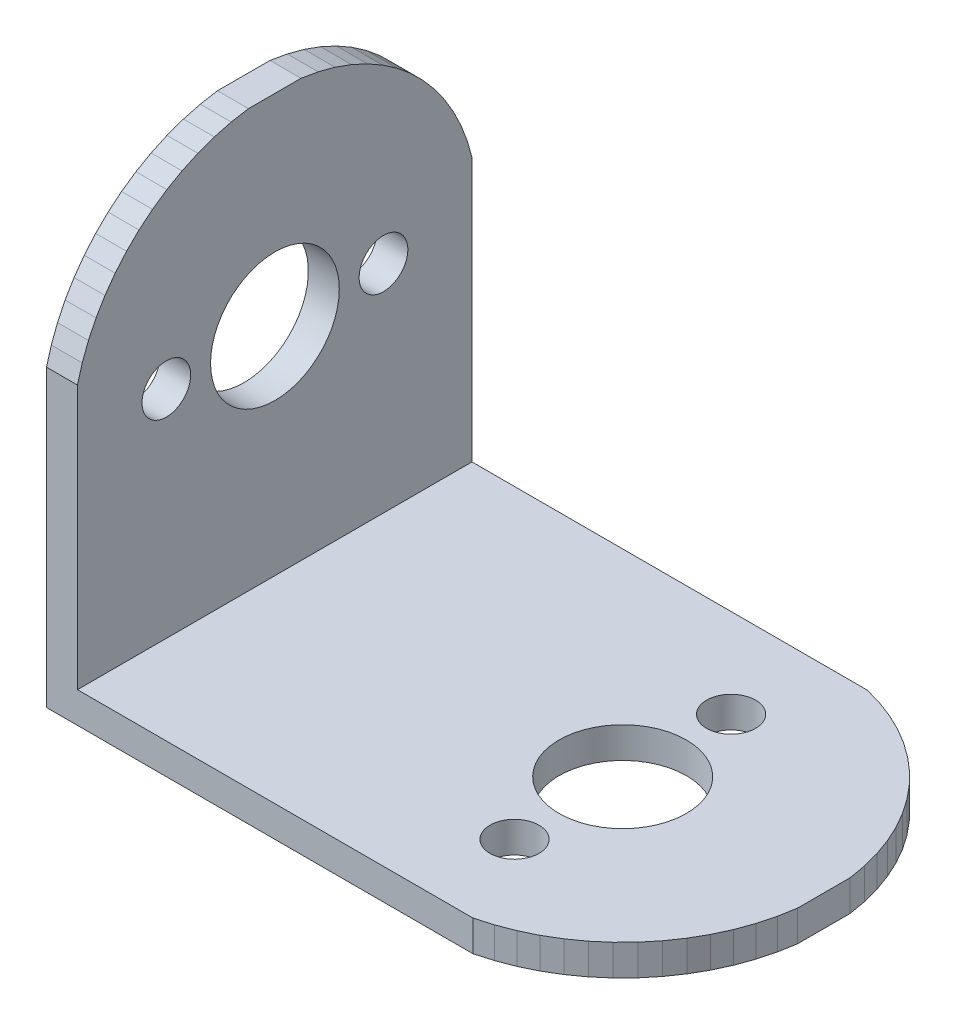
SolidWorks part; units mm, degrees
ref_plane "Alzado" through (0, 0, 0) normal (0, 0, 1) x (1, 0, 0)
ref_plane "Planta" through (0, 0, 0) normal (0, 1, 0) x (1, 0, 0)
ref_plane "Vista lateral" through (0, 0, 0) normal (1, 0, 0) x (0, 0, -1)
ref_plane "Plano1" through (-18.75, 0, 0) normal (-1, 0, 0) x (0, -1, 0)
sketch "Croquis1" plane through (-18.75, 0, 0) normal (-1, 0, 0) x (0, -1, 0)
  line L0 (-19.0529, -77.75) -> (-19.0529, -52.25)
  line L1 (-19.0529, -52.25) -> (-20.1385, -52.5599)
  line L2 (-20.1385, -52.5599) -> (-21.1933, -52.9621)
  line L3 (-21.1933, -52.9621) -> (-22.2097, -53.4535)
  line L4 (-22.2097, -53.4535) -> (-23.18, -54.0305)
  line L5 (-23.18, -54.0305) -> (-24.0971, -54.6889)
  line L6 (-24.0971, -54.6889) -> (-24.9542, -55.4237)
  line L7 (-24.9542, -55.4237) -> (-25.7448, -56.2295)
  line L8 (-25.7448, -56.2295) -> (-26.4632, -57.1004)
  line L9 (-26.4632, -57.1004) -> (-27.104, -58.0298)
  line L10 (-27.104, -58.0298) -> (-27.6625, -59.0109)
  line L11 (-27.6625, -59.0109) -> (-28.1345, -60.0365)
  line L12 (-28.1345, -60.0365) -> (-28.5165, -61.0988)
  line L13 (-28.5165, -61.0988) -> (-28.8057, -62.1901)
  line L14 (-28.8057, -62.1901) -> (-29, -63.3022)
  line L15 (-29, -63.3022) -> (-29, -66.6978)
  line L16 (-29, -66.6978) -> (-28.8057, -67.8099)
  line L17 (-28.8057, -67.8099) -> (-28.5165, -68.9012)
  line L18 (-28.5165, -68.9012) -> (-28.1345, -69.9635)
  line L19 (-28.1345, -69.9635) -> (-27.6625, -70.9891)
  line L20 (-27.6625, -70.9891) -> (-27.104, -71.9702)
  line L21 (-27.104, -71.9702) -> (-26.4632, -72.8996)
  line L22 (-26.4632, -72.8996) -> (-25.7448, -73.7705)
  line L23 (-25.7448, -73.7705) -> (-24.9542, -74.5763)
  line L24 (-24.9542, -74.5763) -> (-24.0971, -75.3111)
  line L25 (-24.0971, -75.3111) -> (-23.18, -75.9695)
  line L26 (-23.18, -75.9695) -> (-22.2097, -76.5465)
  line L27 (-22.2097, -76.5465) -> (-21.1933, -77.0379)
  line L28 (-21.1933, -77.0379) -> (-20.1385, -77.4401)
  line L29 (-20.1385, -77.4401) -> (-19.0529, -77.75)
extrude "Saliente-Extruir1" add sketch "Croquis1" against normal blind 2
sketch "Croquis2" plane through (0, 19.0529, 0) normal (0, -1, 0) x (1, 0, 0)
  line L0 (-16.75, -52.25) -> (-16.75, -77.75)
  line L1 (-16.75, -77.75) -> (-18.75, -77.75)
  line L2 (-18.75, -77.75) -> (-18.75, -52.25)
  line L3 (-18.75, -52.25) -> (-16.75, -52.25)
extrude "Saliente-Extruir2" add sketch "Croquis2" along normal blind 17.0529
sketch "Croquis3" plane through (0, 2, 0) normal (0, -1, 0) x (1, 0, 0)
  line L0 (8.8029, -77.75) -> (-18.75, -77.75)
  line L1 (-18.75, -77.75) -> (-18.75, -52.25)
  line L2 (-18.75, -52.25) -> (8.8029, -52.25)
  line L3 (8.8029, -52.25) -> (9.8885, -52.5599)
  line L4 (9.8885, -52.5599) -> (10.9433, -52.9621)
  line L5 (10.9433, -52.9621) -> (11.9597, -53.4535)
  line L6 (11.9597, -53.4535) -> (12.93, -54.0305)
  line L7 (12.93, -54.0305) -> (13.8471, -54.6889)
  line L8 (13.8471, -54.6889) -> (14.7042, -55.4237)
  line L9 (14.7042, -55.4237) -> (15.4948, -56.2295)
  line L10 (15.4948, -56.2295) -> (16.2132, -57.1004)
  line L11 (16.2132, -57.1004) -> (16.854, -58.0298)
  line L12 (16.854, -58.0298) -> (17.4125, -59.0109)
  line L13 (17.4125, -59.0109) -> (17.8845, -60.0365)
  line L14 (17.8845, -60.0365) -> (18.2665, -61.0988)
  line L15 (18.2665, -61.0988) -> (18.5557, -62.1901)
  line L16 (18.5557, -62.1901) -> (18.75, -63.3022)
  line L17 (18.75, -63.3022) -> (18.75, -66.6978)
  line L18 (18.75, -66.6978) -> (18.5557, -67.8099)
  line L19 (18.5557, -67.8099) -> (18.2665, -68.9012)
  line L20 (18.2665, -68.9012) -> (17.8845, -69.9635)
  line L21 (17.8845, -69.9635) -> (17.4125, -70.9891)
  line L22 (17.4125, -70.9891) -> (16.854, -71.9702)
  line L23 (16.854, -71.9702) -> (16.2132, -72.8996)
  line L24 (16.2132, -72.8996) -> (15.4948, -73.7705)
  line L25 (15.4948, -73.7705) -> (14.7042, -74.5763)
  line L26 (14.7042, -74.5763) -> (13.8471, -75.3111)
  line L27 (13.8471, -75.3111) -> (12.93, -75.9695)
  line L28 (12.93, -75.9695) -> (11.9597, -76.5465)
  line L29 (11.9597, -76.5465) -> (10.9433, -77.0379)
  line L30 (10.9433, -77.0379) -> (9.8885, -77.4401)
  line L31 (9.8885, -77.4401) -> (8.8029, -77.75)
extrude "Saliente-Extruir3" add sketch "Croquis3" along normal blind 2
sketch "Croquis4" plane through (-18.75, 0, 0) normal (-1, 0, 0) x (0, 0, 1)
  line L0 (-67.8848, 13.2291) -> (-67.403, 12.8022)
  line L1 (-67.403, 12.8022) -> (-66.8589, 12.4582)
  line L2 (-66.8589, 12.4582) -> (-66.2667, 12.2059)
  line L3 (-66.2667, 12.2059) -> (-65.6416, 12.0518)
  line L4 (-65.6416, 12.0518) -> (-65, 12)
  line L5 (-65, 12) -> (-64.3584, 12.0518)
  line L6 (-64.3584, 12.0518) -> (-63.7333, 12.2059)
  line L7 (-63.7333, 12.2059) -> (-63.1411, 12.4582)
  line L8 (-63.1411, 12.4582) -> (-62.597, 12.8022)
  line L9 (-62.597, 12.8022) -> (-62.1152, 13.2291)
  line L10 (-62.1152, 13.2291) -> (-61.7081, 13.7277)
  line L11 (-61.7081, 13.7277) -> (-61.3862, 14.2852)
  line L12 (-61.3862, 14.2852) -> (-61.1579, 14.8871)
  line L13 (-61.1579, 14.8871) -> (-61.0292, 15.5179)
  line L14 (-61.0292, 15.5179) -> (-61.0032, 16.1611)
  line L15 (-61.0032, 16.1611) -> (-61.0808, 16.8001)
  line L16 (-61.0808, 16.8001) -> (-61.2599, 17.4184)
  line L17 (-61.2599, 17.4184) -> (-61.5359, 18)
  line L18 (-61.5359, 18) -> (-61.9016, 18.5298)
  line L19 (-61.9016, 18.5298) -> (-62.3475, 18.994)
  line L20 (-62.3475, 18.994) -> (-62.8621, 19.3808)
  line L21 (-62.8621, 19.3808) -> (-63.4321, 19.6799)
  line L22 (-63.4321, 19.6799) -> (-64.0427, 19.8838)
  line L23 (-64.0427, 19.8838) -> (-64.6781, 19.987)
  line L24 (-64.6781, 19.987) -> (-65.3219, 19.987)
  line L25 (-65.3219, 19.987) -> (-65.9573, 19.8838)
  line L26 (-65.9573, 19.8838) -> (-66.5679, 19.6799)
  line L27 (-66.5679, 19.6799) -> (-67.1379, 19.3808)
  line L28 (-67.1379, 19.3808) -> (-67.6525, 18.994)
  line L29 (-67.6525, 18.994) -> (-68.0984, 18.5298)
  line L30 (-68.0984, 18.5298) -> (-68.4641, 18)
  line L31 (-68.4641, 18) -> (-68.7401, 17.4184)
  line L32 (-68.7401, 17.4184) -> (-68.9192, 16.8001)
  line L33 (-68.9192, 16.8001) -> (-68.9968, 16.1611)
  line L34 (-68.9968, 16.1611) -> (-68.9708, 15.5179)
  line L35 (-68.9708, 15.5179) -> (-68.8421, 14.8871)
  line L36 (-68.8421, 14.8871) -> (-68.6138, 14.2852)
  line L37 (-68.6138, 14.2852) -> (-68.2919, 13.7277)
  line L38 (-68.2919, 13.7277) -> (-67.8848, 13.2291)
extrude "Cortar-Extruir1" cut sketch "Croquis4" against normal through all
sketch "Croquis5" plane through (-18.75, 0, 0) normal (-1, 0, 0) x (0, 0, 1)
  line L0 (-57.25, 14.701) -> (-56.9393, 14.9393)
  line L1 (-56.9393, 14.9393) -> (-56.701, 15.25)
  line L2 (-56.701, 15.25) -> (-56.5511, 15.6118)
  line L3 (-56.5511, 15.6118) -> (-56.5, 16)
  line L4 (-56.5, 16) -> (-56.5511, 16.3882)
  line L5 (-56.5511, 16.3882) -> (-56.701, 16.75)
  line L6 (-56.701, 16.75) -> (-56.9393, 17.0607)
  line L7 (-56.9393, 17.0607) -> (-57.25, 17.299)
  line L8 (-57.25, 17.299) -> (-57.6118, 17.4489)
  line L9 (-57.6118, 17.4489) -> (-58, 17.5)
  line L10 (-58, 17.5) -> (-58.3882, 17.4489)
  line L11 (-58.3882, 17.4489) -> (-58.75, 17.299)
  line L12 (-58.75, 17.299) -> (-59.0607, 17.0607)
  line L13 (-59.0607, 17.0607) -> (-59.299, 16.75)
  line L14 (-59.299, 16.75) -> (-59.4489, 16.3882)
  line L15 (-59.4489, 16.3882) -> (-59.5, 16)
  line L16 (-59.5, 16) -> (-59.4489, 15.6118)
  line L17 (-59.4489, 15.6118) -> (-59.299, 15.25)
  line L18 (-59.299, 15.25) -> (-59.0607, 14.9393)
  line L19 (-59.0607, 14.9393) -> (-58.75, 14.701)
  line L20 (-58.75, 14.701) -> (-58.3882, 14.5511)
  line L21 (-58.3882, 14.5511) -> (-58, 14.5)
  line L22 (-58, 14.5) -> (-57.6118, 14.5511)
  line L23 (-57.6118, 14.5511) -> (-57.25, 14.701)
extrude "Cortar-Extruir2" cut sketch "Croquis5" against normal through all
sketch "Croquis6" plane through (0, 2, 0) normal (0, 1, 0) x (-1, 0, 0)
  line L0 (-4.451, -57.25) -> (-4.6893, -56.9393)
  line L1 (-4.6893, -56.9393) -> (-5, -56.701)
  line L2 (-5, -56.701) -> (-5.3618, -56.5511)
  line L3 (-5.3618, -56.5511) -> (-5.75, -56.5)
  line L4 (-5.75, -56.5) -> (-6.1382, -56.5511)
  line L5 (-6.1382, -56.5511) -> (-6.5, -56.701)
  line L6 (-6.5, -56.701) -> (-6.8107, -56.9393)
  line L7 (-6.8107, -56.9393) -> (-7.049, -57.25)
  line L8 (-7.049, -57.25) -> (-7.1989, -57.6118)
  line L9 (-7.1989, -57.6118) -> (-7.25, -58)
  line L10 (-7.25, -58) -> (-7.1989, -58.3882)
  line L11 (-7.1989, -58.3882) -> (-7.049, -58.75)
  line L12 (-7.049, -58.75) -> (-6.8107, -59.0607)
  line L13 (-6.8107, -59.0607) -> (-6.5, -59.299)
  line L14 (-6.5, -59.299) -> (-6.1382, -59.4489)
  line L15 (-6.1382, -59.4489) -> (-5.75, -59.5)
  line L16 (-5.75, -59.5) -> (-5.3618, -59.4489)
  line L17 (-5.3618, -59.4489) -> (-5, -59.299)
  line L18 (-5, -59.299) -> (-4.6893, -59.0607)
  line L19 (-4.6893, -59.0607) -> (-4.451, -58.75)
  line L20 (-4.451, -58.75) -> (-4.3011, -58.3882)
  line L21 (-4.3011, -58.3882) -> (-4.25, -58)
  line L22 (-4.25, -58) -> (-4.3011, -57.6118)
  line L23 (-4.3011, -57.6118) -> (-4.451, -57.25)
extrude "Cortar-Extruir3" cut sketch "Croquis6" against normal through all
sketch "Croquis7" plane through (0, 2, 0) normal (0, 1, 0) x (-1, 0, 0)
  line L0 (-5.75, -73.5) -> (-5.3618, -73.4489)
  line L1 (-5.3618, -73.4489) -> (-5, -73.299)
  line L2 (-5, -73.299) -> (-4.6893, -73.0607)
  line L3 (-4.6893, -73.0607) -> (-4.451, -72.75)
  line L4 (-4.451, -72.75) -> (-4.3011, -72.3882)
  line L5 (-4.3011, -72.3882) -> (-4.25, -72)
  line L6 (-4.25, -72) -> (-4.3011, -71.6118)
  line L7 (-4.3011, -71.6118) -> (-4.451, -71.25)
  line L8 (-4.451, -71.25) -> (-4.6893, -70.9393)
  line L9 (-4.6893, -70.9393) -> (-5, -70.701)
  line L10 (-5, -70.701) -> (-5.3618, -70.5511)
  line L11 (-5.3618, -70.5511) -> (-5.75, -70.5)
  line L12 (-5.75, -70.5) -> (-6.1382, -70.5511)
  line L13 (-6.1382, -70.5511) -> (-6.5, -70.701)
  line L14 (-6.5, -70.701) -> (-6.8107, -70.9393)
  line L15 (-6.8107, -70.9393) -> (-7.049, -71.25)
  line L16 (-7.049, -71.25) -> (-7.1989, -71.6118)
  line L17 (-7.1989, -71.6118) -> (-7.25, -72)
  line L18 (-7.25, -72) -> (-7.1989, -72.3882)
  line L19 (-7.1989, -72.3882) -> (-7.049, -72.75)
  line L20 (-7.049, -72.75) -> (-6.8107, -73.0607)
  line L21 (-6.8107, -73.0607) -> (-6.5, -73.299)
  line L22 (-6.5, -73.299) -> (-6.1382, -73.4489)
  line L23 (-6.1382, -73.4489) -> (-5.75, -73.5)
extrude "Cortar-Extruir4" cut sketch "Croquis7" against normal through all
sketch "Croquis8" plane through (0, 2, 0) normal (0, 1, 0) x (-1, 0, 0)
  line L0 (-2.2082, -63.1411) -> (-2.5522, -62.597)
  line L1 (-2.5522, -62.597) -> (-2.9791, -62.1152)
  line L2 (-2.9791, -62.1152) -> (-3.4777, -61.7081)
  line L3 (-3.4777, -61.7081) -> (-4.0352, -61.3862)
  line L4 (-4.0352, -61.3862) -> (-4.6371, -61.1579)
  line L5 (-4.6371, -61.1579) -> (-5.2679, -61.0292)
  line L6 (-5.2679, -61.0292) -> (-5.9111, -61.0032)
  line L7 (-5.9111, -61.0032) -> (-6.5501, -61.0808)
  line L8 (-6.5501, -61.0808) -> (-7.1684, -61.2599)
  line L9 (-7.1684, -61.2599) -> (-7.75, -61.5359)
  line L10 (-7.75, -61.5359) -> (-8.2798, -61.9016)
  line L11 (-8.2798, -61.9016) -> (-8.744, -62.3475)
  line L12 (-8.744, -62.3475) -> (-9.1308, -62.8621)
  line L13 (-9.1308, -62.8621) -> (-9.4299, -63.4321)
  line L14 (-9.4299, -63.4321) -> (-9.6338, -64.0427)
  line L15 (-9.6338, -64.0427) -> (-9.737, -64.6781)
  line L16 (-9.737, -64.6781) -> (-9.737, -65.3219)
  line L17 (-9.737, -65.3219) -> (-9.6338, -65.9573)
  line L18 (-9.6338, -65.9573) -> (-9.4299, -66.5679)
  line L19 (-9.4299, -66.5679) -> (-9.1308, -67.1379)
  line L20 (-9.1308, -67.1379) -> (-8.744, -67.6525)
  line L21 (-8.744, -67.6525) -> (-8.2798, -68.0984)
  line L22 (-8.2798, -68.0984) -> (-7.75, -68.4641)
  line L23 (-7.75, -68.4641) -> (-7.1684, -68.7401)
  line L24 (-7.1684, -68.7401) -> (-6.5501, -68.9192)
  line L25 (-6.5501, -68.9192) -> (-5.9111, -68.9968)
  line L26 (-5.9111, -68.9968) -> (-5.2679, -68.9708)
  line L27 (-5.2679, -68.9708) -> (-4.6371, -68.8421)
  line L28 (-4.6371, -68.8421) -> (-4.0352, -68.6138)
  line L29 (-4.0352, -68.6138) -> (-3.4777, -68.2919)
  line L30 (-3.4777, -68.2919) -> (-2.9791, -67.8848)
  line L31 (-2.9791, -67.8848) -> (-2.5522, -67.403)
  line L32 (-2.5522, -67.403) -> (-2.2082, -66.8589)
  line L33 (-2.2082, -66.8589) -> (-1.9559, -66.2667)
  line L34 (-1.9559, -66.2667) -> (-1.8018, -65.6416)
  line L35 (-1.8018, -65.6416) -> (-1.75, -65)
  line L36 (-1.75, -65) -> (-1.8018, -64.3584)
  line L37 (-1.8018, -64.3584) -> (-1.9559, -63.7333)
  line L38 (-1.9559, -63.7333) -> (-2.2082, -63.1411)
extrude "Cortar-Extruir5" cut sketch "Croquis8" against normal through all
sketch "Croquis9" plane through (-16.75, 0, 0) normal (1, 0, 0) x (0, 0, -1)
  line L0 (72.75, 14.701) -> (73.0607, 14.9393)
  line L1 (73.0607, 14.9393) -> (73.299, 15.25)
  line L2 (73.299, 15.25) -> (73.4489, 15.6118)
  line L3 (73.4489, 15.6118) -> (73.5, 16)
  line L4 (73.5, 16) -> (73.4489, 16.3882)
  line L5 (73.4489, 16.3882) -> (73.299, 16.75)
  line L6 (73.299, 16.75) -> (73.0607, 17.0607)
  line L7 (73.0607, 17.0607) -> (72.75, 17.299)
  line L8 (72.75, 17.299) -> (72.3882, 17.4489)
  line L9 (72.3882, 17.4489) -> (72, 17.5)
  line L10 (72, 17.5) -> (71.6118, 17.4489)
  line L11 (71.6118, 17.4489) -> (71.25, 17.299)
  line L12 (71.25, 17.299) -> (70.9393, 17.0607)
  line L13 (70.9393, 17.0607) -> (70.701, 16.75)
  line L14 (70.701, 16.75) -> (70.5511, 16.3882)
  line L15 (70.5511, 16.3882) -> (70.5, 16)
  line L16 (70.5, 16) -> (70.5511, 15.6118)
  line L17 (70.5511, 15.6118) -> (70.701, 15.25)
  line L18 (70.701, 15.25) -> (70.9393, 14.9393)
  line L19 (70.9393, 14.9393) -> (71.25, 14.701)
  line L20 (71.25, 14.701) -> (71.6118, 14.5511)
  line L21 (71.6118, 14.5511) -> (72, 14.5)
  line L22 (72, 14.5) -> (72.3882, 14.5511)
  line L23 (72.3882, 14.5511) -> (72.75, 14.701)
extrude "Cortar-Extruir6" cut sketch "Croquis9" against normal through all
sketch "Croquis10" plane through (-18.75, 0, 0) normal (-1, 0, 0) x (0, 0, 1)
  line L0 (-65.0137, 15.9633) -> (-65.0137, 23.0429) construction
  circle A0 centre (-65.0137, 15.9633) radius 4.1606
  circle A1 centre (-57.9954, 15.9633) radius 1.5742
  circle A2 centre (-72.032, 15.9633) radius 1.5742
extrude "Cortar-Extruir7" cut sketch "Croquis10" against normal through all
sketch "Croquis11" plane through (0, 0, 0) normal (0, -1, 0) x (1, 0, 0)
  line L0 (1.75, -65) -> (9.737, -65) construction
  line L1 (9.737, -64.6781) -> (9.737, -65.3219) construction
  line L2 (4.25, -58) -> (7.25, -58) construction
  circle A0 centre (5.7435, -65) radius 4.1161
  circle A1 centre (5.75, -58) radius 1.5826
  circle A2 centre (5.75, -72) radius 1.5826
extrude "Cortar-Extruir8" cut sketch "Croquis11" against normal through all
